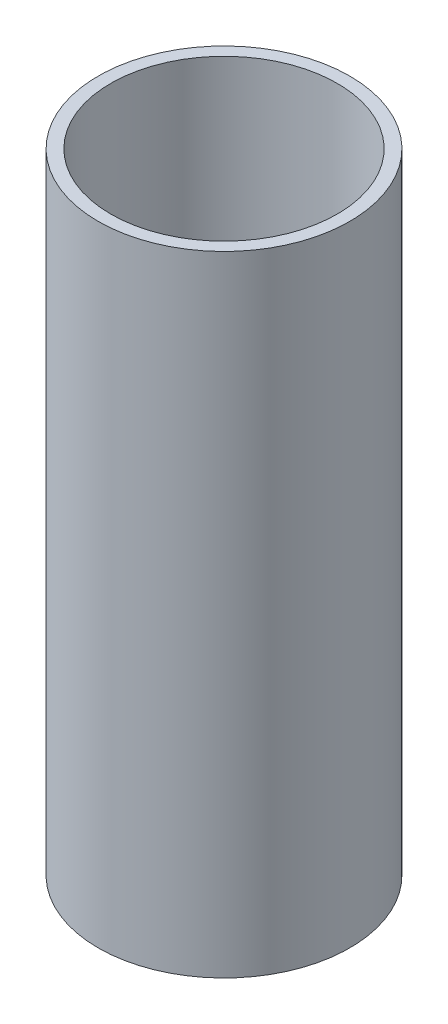
SolidWorks part; units mm, degrees
ref_plane "前视基准面" through (0, 0, 0) normal (0, 0, 1) x (1, 0, 0)
ref_plane "上视基准面" through (0, 0, 0) normal (0, 1, 0) x (1, 0, 0)
ref_plane "右视基准面" through (0, 0, 0) normal (1, 0, 0) x (0, 0, -1)
other "Configuration Table"
sketch "草图1" plane through (0, 0, 0) normal (0, 1, 0) x (1, 0, 0)
  circle A0 centre (0, 0) radius 18
  circle A1 centre (0, 0) radius 20
  dimension "D1" = 40
  dimension "D2" = 36
extrude "凸台-拉伸1" add sketch "草图1" along normal blind 100
